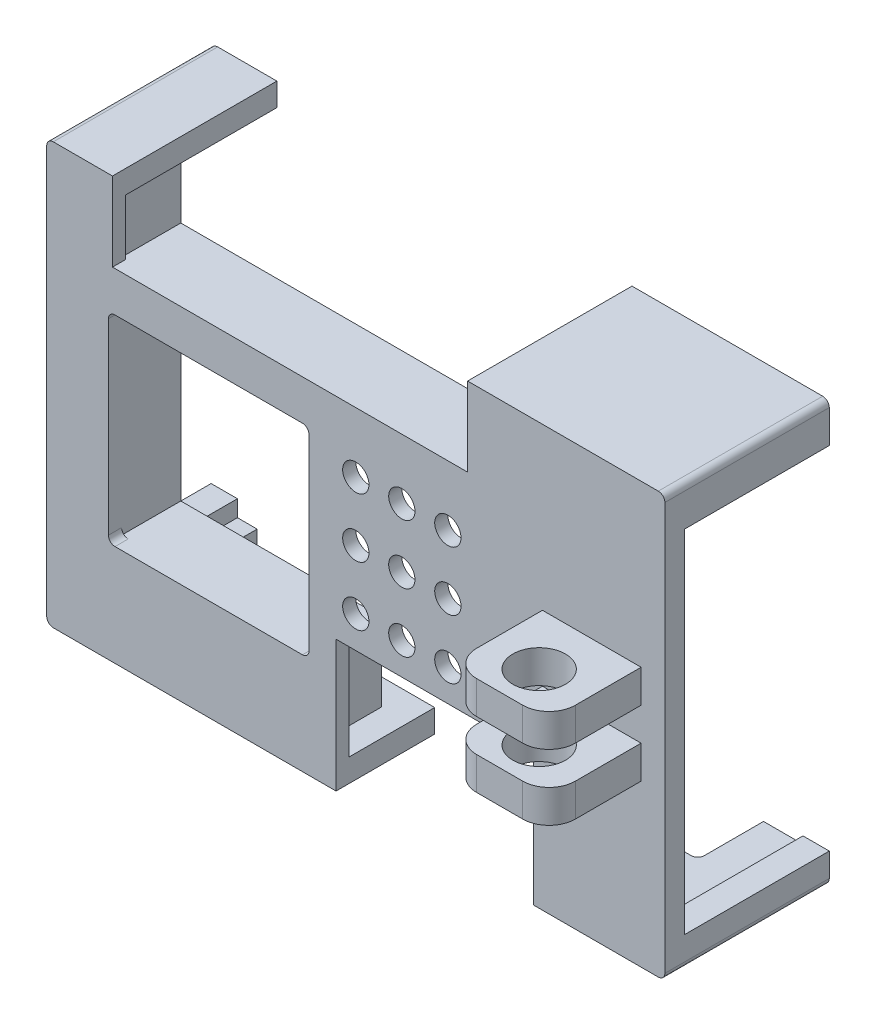
SolidWorks part; units mm, degrees
ref_plane "前视基准面" through (0, 0, 0) normal (0, 0, 1) x (1, 0, 0)
ref_plane "上视基准面" through (0, 0, 0) normal (0, 1, 0) x (1, 0, 0)
ref_plane "右视基准面" through (0, 0, 0) normal (1, 0, 0) x (0, 0, -1)
sketch "草图1" plane through (0, 0, 0) normal (0, 0, 1) x (1, 0, 0)
  line L1 (-47, -32) -> (47, -32)
  line L2 (-47, -32) -> (-47, 32)
  line L3 (-47, 32) -> (47, 32)
  line L4 (47, -32) -> (47, 32)
  line L5 (-47, -32) -> (47, 32) construction
  line L6 (-47, 32) -> (47, -32) construction
  point P0 (0, 0)
  dimension "D1" = 94
  dimension "D2" = 64
extrude "凸台-拉伸1" add sketch "草图1" against normal blind 25
sketch "草图3" plane through (0, 0, -25) normal (0, 0, -1) x (-1, 0, 0)
  line L1 (-43, -28.5) -> (43, -28.5)
  line L2 (-43, -28.5) -> (-43, 28.5)
  line L3 (-43, 28.5) -> (43, 28.5)
  line L4 (43, -28.5) -> (43, 28.5)
  line L5 (-43, -28.5) -> (43, 28.5) construction
  line L6 (-43, 28.5) -> (43, -28.5) construction
  point P0 (0, 0)
  dimension "D1" = 86
  dimension "D2" = 57
extrude "切除-拉伸1" cut sketch "草图3" against normal blind 23
fillet "圆角1" radius 1 4 edges at (-47, 32, -12.5) (-47, -32, -12.5) (47, -32, -12.5) (47, 32, -12.5)
sketch "草图4" plane through (0, -32, 0) normal (0, -1, 0) x (1, 0, 0)
  line L0 (-46, -25) -> (46, -25) construction
  line L1 (-40, -15) -> (37, -15)
  line L2 (-40, -15) -> (-40, -25)
  line L3 (-40, -25) -> (37, -25)
  line L4 (37, -15) -> (37, -25)
  line L5 (-40, -15) -> (37, -25) construction
  line L6 (-40, -25) -> (37, -15) construction
  line L7 (-47, -25) -> (-47, 0) construction
  line L8 (47, 0) -> (47, -25) construction
  point P0 (-1.5, -20)
  dimension "D1" = 10
  dimension "D2" = 10
  dimension "D3" = 0
  dimension "D4" = 7
extrude "切除-拉伸3" cut sketch "草图4" against normal blind 5
fillet "圆角4" radius 1 2 edges at (37, -30.25, -15) (-40, -30.25, -15)
sketch "草图5" plane through (0, 32, 0) normal (0, 1, 0) x (1, 0, 0)
  line L0 (46, 25) -> (-46, 25) construction
  line L1 (17, 0) -> (-37, 0)
  line L2 (17, 0) -> (17, 25)
  line L3 (17, 25) -> (-37, 25)
  line L4 (-37, 0) -> (-37, 25)
  line L5 (46, 0) -> (-46, 0) construction
  line L6 (-47, 0) -> (-47, 25) construction
  line L7 (47, 25) -> (47, 0) construction
  dimension "D1" = 0
  dimension "D2" = 10
  dimension "D3" = 30
extrude "切除-拉伸4" cut sketch "草图5" against normal blind 12
sketch "草图6" plane through (0, 0, 0) normal (0, 0, 1) x (1, 0, 0)
  line L0 (47, -31) -> (47, 31) construction
  line L1 (-3, -12) -> (27, -12)
  line L2 (-3, -12) -> (-3, -32)
  line L3 (-3, -32) -> (27, -32)
  line L4 (27, -12) -> (27, -32)
  line L5 (-3, -12) -> (27, -32) construction
  line L6 (-3, -32) -> (27, -12) construction
  line L7 (-46, -32) -> (46, -32) construction
  point P0 (12, -22)
  dimension "D1" = 20
  dimension "D2" = 0
  dimension "D3" = 20
  dimension "D4" = 30
extrude "切除-拉伸5" cut sketch "草图6" against normal blind 18
sketch "草图7" plane through (-47, 0, 0) normal (-1, 0, 0) x (0, 0, 1)
  line L0 (-25, 31) -> (-25, -31) construction
  line L1 (-3, 26) -> (-25, 26)
  line L2 (-3, 26) -> (-3, -26)
  line L3 (-3, -26) -> (-25, -26)
  line L4 (-25, 26) -> (-25, -26)
  line L5 (-3, 26) -> (-25, -26) construction
  line L6 (-3, -26) -> (-25, 26) construction
  line L7 (0, -32) -> (-25, -32) construction
  line L8 (-25, 32) -> (0, 32) construction
  line L9 (0, 31) -> (0, -31) construction
  point P0 (-14, 0)
  dimension "D1" = 0
  dimension "D2" = 6
  dimension "D3" = 6
  dimension "D4" = 3
extrude "切除-拉伸6" cut sketch "草图7" against normal blind 5
sketch "草图8" plane through (0, 0, 0) normal (0, 0, 1) x (1, 0, 0)
  line L1 (-37.6133, 13.8904) -> (-7.1133, 13.8904)
  line L2 (-37.6133, 13.8904) -> (-37.6133, -16.6096)
  line L3 (-37.6133, -16.6096) -> (-7.1133, -16.6096)
  line L4 (-7.1133, 13.8904) -> (-7.1133, -16.6096)
  line L5 (-37.6133, 13.8904) -> (-7.1133, -16.6096) construction
  line L6 (-37.6133, -16.6096) -> (-7.1133, 13.8904) construction
  point P0 (-22.3633, -1.3596)
  dimension "D1" = 30.5
  dimension "D2" = 30.5
extrude "切除-拉伸7" cut sketch "草图8" against normal blind 5
fillet "圆角5" radius 1 4 edges at (-37.6133, 13.8904, -1) (-7.1133, 13.8904, -1) (-37.6133, -16.6096, -1) (-7.1133, -16.6096, -1)
sketch "草图9" plane through (0, 0, -25) normal (0, 0, -1) x (-1, 0, 0)
  line L0 (47, 31) -> (47, 26) construction
  line L1 (37, 32) -> (46, 32) construction
  line L2 (13.75, 0) -> (-13.75, 0) construction
  line L3 (0, 13.75) -> (0, -13.75) construction
  circle A0 centre (44.7, 29.7) radius 1.55
  circle A1 centre (44.7, -29.7) radius 1.55
  circle A2 centre (-44.7, -29.7) radius 1.55
  circle A3 centre (-44.7, 29.7) radius 1.55
  dimension "D1" = 2.3
  dimension "D2" = 2.3
extrude "切除-拉伸8" cut sketch "草图9" against normal blind 5
sketch "草图10" plane through (0, 0, -25) normal (0, 0, -1) x (-1, 0, 0)
  line L0 (-47, -31) -> (-47, 31) construction
  line L1 (-47, 26) -> (-43, 26)
  line L2 (-47, 26) -> (-47, -27.4)
  line L3 (-47, -27.4) -> (-43, -27.4)
  line L4 (-43, 26) -> (-43, -27.4)
  line L5 (-43, 28.5) -> (-43, -28.5) construction
  line L6 (-37, -32) -> (-46, -32) construction
  line L7 (-46, 32) -> (-17, 32) construction
  dimension "D1" = 4.6
  dimension "D2" = 6
extrude "切除-拉伸9" cut sketch "草图10" against normal blind 22
sketch "草图11" plane through (0, 0, -2) normal (0, 0, -1) x (-1, 0, 0)
  line L0 (3, -28.5) -> (39, -28.5) construction
  line L1 (7.1133, -16.6096) -> (37.6133, -16.6096)
  line L2 (7.1133, -16.6096) -> (7.1133, -28.5)
  line L3 (7.1133, -28.5) -> (37.6133, -28.5)
  line L4 (37.6133, -16.6096) -> (37.6133, -28.5)
  line L5 (36.6133, -16.6096) -> (8.1133, -16.6096) construction
  line L7 (7.1133, -15.6096) -> (7.1133, 12.8904) construction
  line L8 (37.6133, 12.8904) -> (37.6133, -15.6096) construction
  dimension "D1" = 0
  dimension "D2" = 0
  dimension "D3" = 0
extrude "凸台-拉伸2" add sketch "草图11" along normal blind 9
sketch "草图12" plane through (0, 0, -2) normal (0, 0, -1) x (-1, 0, 0)
  line L0 (8.1133, 13.8904) -> (36.6133, 13.8904) construction
  line L1 (-17, 20) -> (37.6133, 20)
  line L2 (-17, 20) -> (-17, 13.8904)
  line L3 (-17, 13.8904) -> (37.6133, 13.8904)
  line L4 (37.6133, 20) -> (37.6133, 13.8904)
  line L5 (37.6133, -28.5) -> (43, -28.5) construction
  line L6 (37.6133, 28.5) -> (43, 28.5)
  line L7 (37.6133, 28.5) -> (37.6133, -28.5)
  line L8 (37.6133, -28.5) -> (43, -28.5)
  line L9 (43, 28.5) -> (43, -28.5)
  line L10 (43, -28.5) -> (43, 28.5) construction
  line L11 (37.6133, 12.8904) -> (37.6133, -15.6096) construction
  line L12 (43, 28.5) -> (37, 28.5) construction
  line L13 (-17, 20) -> (37, 20) construction
  line L14 (-17, 20) -> (-17, 28.5) construction
  line L15 (-47, 26) -> (-47, -27.4) construction
  line L16 (-25, 28.5) -> (-17, 28.5)
  line L17 (-25, 28.5) -> (-25, 1.5)
  line L18 (-25, 1.5) -> (-17, 1.5)
  line L19 (-17, 28.5) -> (-17, 1.5)
  line L20 (-17, 28.5) -> (-43, 28.5) construction
  line L21 (-36, -28.5) -> (-27, -28.5) construction
  dimension "D1" = 0
  dimension "D2" = 0
  dimension "D3" = 0
  dimension "D4" = 0
  dimension "D5" = 0
  dimension "D6" = 22
  dimension "D7" = 0
  dimension "D8" = 0
  dimension "D9" = 30
  dimension "D10" = 0
extrude "凸台-拉伸3" add sketch "草图12" along normal blind 9 contours L17 L18 L19 L16 | L3 L4 L1 L2 | L7 L8 L9 L6
sketch "草图13" plane through (0, 0, 0) normal (0, 0, 1) x (1, 0, 0)
  circle A0 centre (0, 10.839) radius 2
  circle A1 centre (7, 10.839) radius 2
  circle A2 centre (14, 10.839) radius 2
  circle A3 centre (7, 1.839) radius 2
  circle A4 centre (14, 1.839) radius 2
  circle A5 centre (7, -7.161) radius 2
  circle A6 centre (14, -7.161) radius 2
  circle A7 centre (0, 1.839) radius 2
  circle A8 centre (0, -7.161) radius 2
  dimension "D1" = 3
  dimension "D2" = 3
extrude "切除-拉伸10" cut sketch "草图13" against normal blind 10
sketch "草图14" plane through (0, 0, 0) normal (0, 0, 1) x (1, 0, 0)
  line L0 (47, 0) -> (-47, 0) construction
  line L1 (28.3858, 7.5) -> (43.3858, 7.5)
  line L2 (28.3858, 7.5) -> (28.3858, -7.5)
  line L3 (28.3858, -7.5) -> (43.3858, -7.5)
  line L4 (43.3858, 7.5) -> (43.3858, -7.5)
  line L5 (28.3858, 7.5) -> (43.3858, -7.5) construction
  line L6 (28.3858, -7.5) -> (43.3858, 7.5) construction
  line L7 (47, -31) -> (47, 31) construction
  line L8 (-47, 31) -> (-47, -31) construction
  point P0 (35.8858, 0)
  point P15 (35.8858, 0)
  dimension "D1" = 15
  dimension "D2" = 15
extrude "凸台-拉伸4" add sketch "草图14" along normal blind 14
sketch "草图17" plane through (0, -7.5, 0) normal (0, -1, 0) x (1, 0, 0)
  line L0 (43.3858, 14) -> (43.3858, 0) construction
  line L1 (28.3858, 14) -> (43.3858, 14) construction
  circle A0 centre (35.8858, 8) radius 4
  point P6 (38.3858, 8)
  dimension "D1" = 7.5
  dimension "D2" = 6
extrude "切除-拉伸13" cut sketch "草图17" against normal through all
fillet "圆角7" radius 4 2 edges at (28.3858, 0, 14) (43.3858, 0, 14)
sketch "草图18" plane through (0, 0, 0) normal (0, 0, 1) x (1, 0, 0)
  line L0 (28.3858, 7.5) -> (28.3858, -7.5) construction
  line L1 (28.3858, 2.5) -> (43.3858, 2.5)
  line L2 (28.3858, 2.5) -> (28.3858, -2.5)
  line L3 (28.3858, -2.5) -> (43.3858, -2.5)
  line L4 (43.3858, 2.5) -> (43.3858, -2.5)
  line L5 (43.3858, -7.5) -> (43.3858, 7.5) construction
  line L6 (43.3858, 7.5) -> (28.3858, 7.5) construction
  dimension "D1" = 5
  dimension "D2" = 5
extrude "切除-拉伸14" cut sketch "草图18" along normal through all
